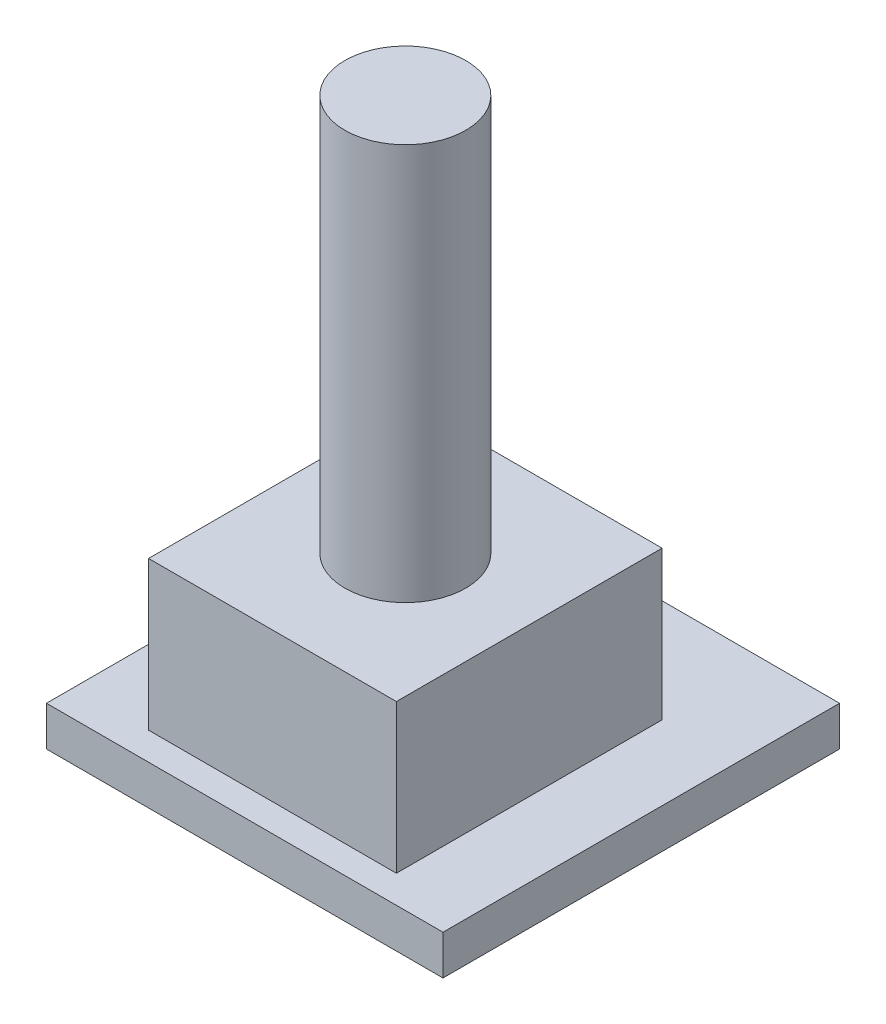
SolidWorks part; units mm, degrees
ref_plane "Front Plane" through (0, 0, 0) normal (0, 0, 1) x (1, 0, 0)
ref_plane "Top Plane" through (0, 0, 0) normal (0, 1, 0) x (1, 0, 0)
ref_plane "Right Plane" through (0, 0, 0) normal (1, 0, 0) x (0, 0, -1)
sketch "Sketch2" plane through (0, 0, 0) normal (0, 1, 0) x (1, 0, 0)
  line L1 (-6.25, -6.7) -> (6.25, -6.7)
  line L2 (-6.25, -6.7) -> (-6.25, 6.7)
  line L3 (-6.25, 6.7) -> (6.25, 6.7)
  line L4 (6.25, -6.7) -> (6.25, 6.7)
  line L5 (-6.25, -6.7) -> (6.25, 6.7) construction
  line L6 (-6.25, 6.7) -> (6.25, -6.7) construction
  point P0 (0, 0)
  dimension "D1" = 12.5
  dimension "D2" = 13.4
extrude "Boss-Extrude1" add sketch "Sketch2" along normal blind 7.5
sketch "Sketch3" plane through (0, 7.5, 0) normal (0, 1, 0) x (1, 0, 0)
  circle A0 centre (0, 0) radius 3.05
  dimension "D1" = 6.1
extrude "Boss-Extrude2" add sketch "Sketch3" along normal blind 20
sketch "Sketch4" plane through (0, 0, 0) normal (0, -1, 0) x (1, 0, 0)
  line L1 (-10, 8.1) -> (10, 8.1)
  line L2 (-10, 8.1) -> (-10, -11.9)
  line L3 (-10, -11.9) -> (10, -11.9)
  line L4 (10, 8.1) -> (10, -11.9)
  point P7 (-4.6057, -0.1497)
  point P8 (-3.9332, 1.0211)
  dimension "D1" = 20
  dimension "D2" = 20
  dimension "D3" = 11.9
  dimension "D4" = 10
extrude "Boss-Extrude3" add sketch "Sketch4" along normal blind 2
